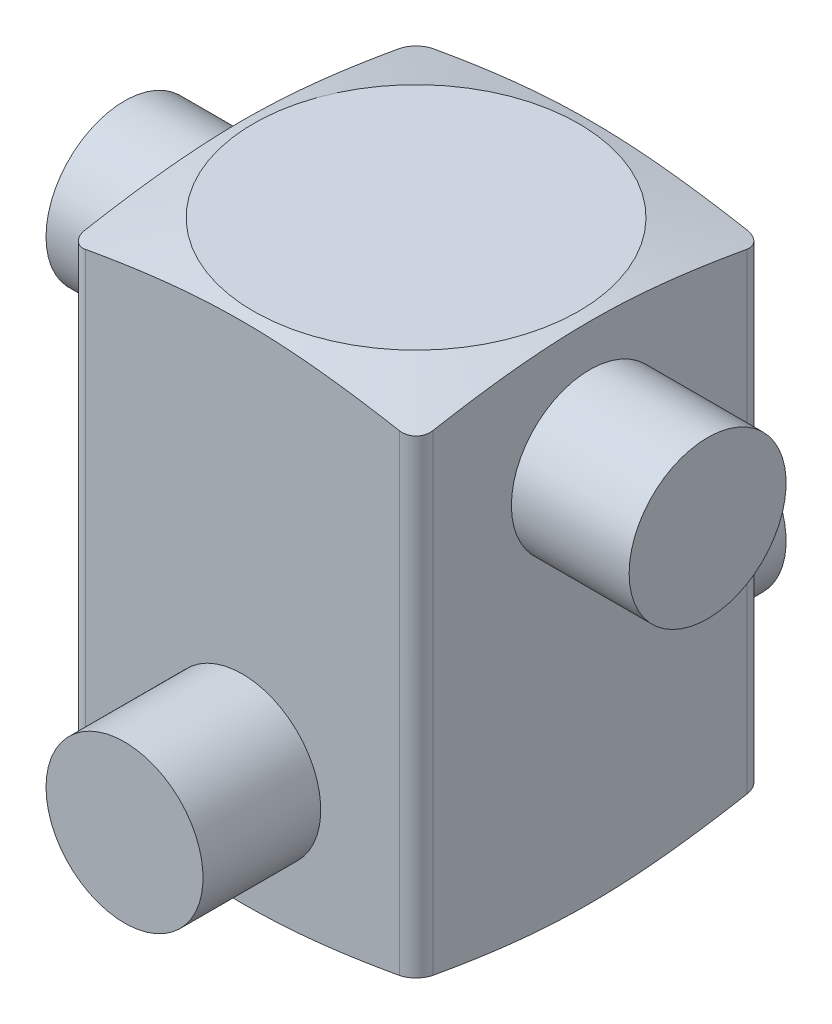
SolidWorks part; units mm, degrees
material "AISI Type A2 Tool Steel"
ref_plane "FRONT" through (0, 0, 0) normal (0, 0, 1) x (1, 0, 0)
ref_plane "TOP" through (0, 0, 0) normal (0, 1, 0) x (1, 0, 0)
ref_plane "SIDE" through (0, 0, 0) normal (1, 0, 0) x (0, 0, -1)
sketch "Intermediate_Body-Sk" plane through (0, 0, 0) normal (0, 1, 0) x (1, 0, 0)
  line L1 (-3.937, -3.937) -> (3.937, -3.937)
  line L2 (-3.937, -3.937) -> (-3.937, 3.937)
  line L3 (-3.937, 3.937) -> (3.937, 3.937)
  line L4 (3.937, -3.937) -> (3.937, 3.937)
  line L5 (-3.937, -3.937) -> (3.937, 3.937) construction
  line L6 (-3.937, 3.937) -> (3.937, -3.937) construction
  point P0 (0, 0)
  dimension "DimA" = 7.874
extrude "Intermediate_Body" add sketch "Intermediate_Body-Sk" along normal blind 11.557
sketch "Rev-CutSk" plane through (0, 0, 0) normal (0, 0, 1) x (1, 0, 0)
  line L0 (-3.683, 11.557) -> (-10.033, 9.8555)
  line L1 (-3.937, 11.557) -> (3.937, 11.557) construction
  line L2 (-10.033, 9.8555) -> (-10.033, 1.7015)
  line L3 (-10.033, 1.7015) -> (-3.683, 0)
  line L4 (4.3307, 0) -> (-4.3307, 0) construction
  line L5 (-3.683, 0) -> (-3.683, 11.557) construction
  line L6 (-3.937, 11.557) -> (-3.937, 0) construction
  line L7 (-3.683, 11.557) -> (-12.573, 11.557)
  line L8 (-12.573, 11.557) -> (-12.573, 0)
  line L9 (-12.573, 0) -> (-3.683, 0)
  line L10 (0, 0) -> (0, 11.557) construction
  dimension "D1" = 15
  dimension "D2" = 0.254
  dimension "D3" = 6.35
  dimension "D4" = 2.54
revolve "Cut-Revolve2" cut sketch "Rev-CutSk" angle 360 about L10
sketch "Pin1" plane through (0, 0, 0) normal (0, 0, 1) x (1, 0, 0)
  line L0 (0, -6.3563) -> (0, 6.3563) construction
  line L1 (13.2016, 0) -> (-13.2016, 0) construction
  circle A0 centre (0, 2.794) radius 1.778
  dimension "Pin_Dia" = 3.556
  dimension "Pin_Dist" = 2.794
extrude "Pin-Extrude1" add sketch "Pin1" along normal mid plane 13.208
sketch "Pin2" plane through (0, 0, 0) normal (1, 0, 0) x (0, 0, -1)
  line L0 (0, 6.3563) -> (0, -6.3563) construction
  line L1 (3.683, 11.557) -> (-3.683, 11.557) construction
  circle A0 centre (0, 8.763) radius 1.778
  dimension "D1" = 3.556
  dimension "D2" = 2.794
extrude "Pin-Extrude2" add sketch "Pin2" along normal mid plane 13.208
fillet "Fillet1" radius 0.381 4 edges at (3.937, 5.7785, -3.937) (-3.937, 5.7785, -3.937) (-3.937, 5.7785, 3.937) (3.937, 5.7785, 3.937)
equation "\"D1@Pin2\"=\"Pin_Dia@Pin1\""
equation "\"D2@Pin2\"=\"Pin_Dist@Pin1\""
equation "\"D1@Pin-Extrude2\"=\"UDIA@Pin-Extrude1\""
